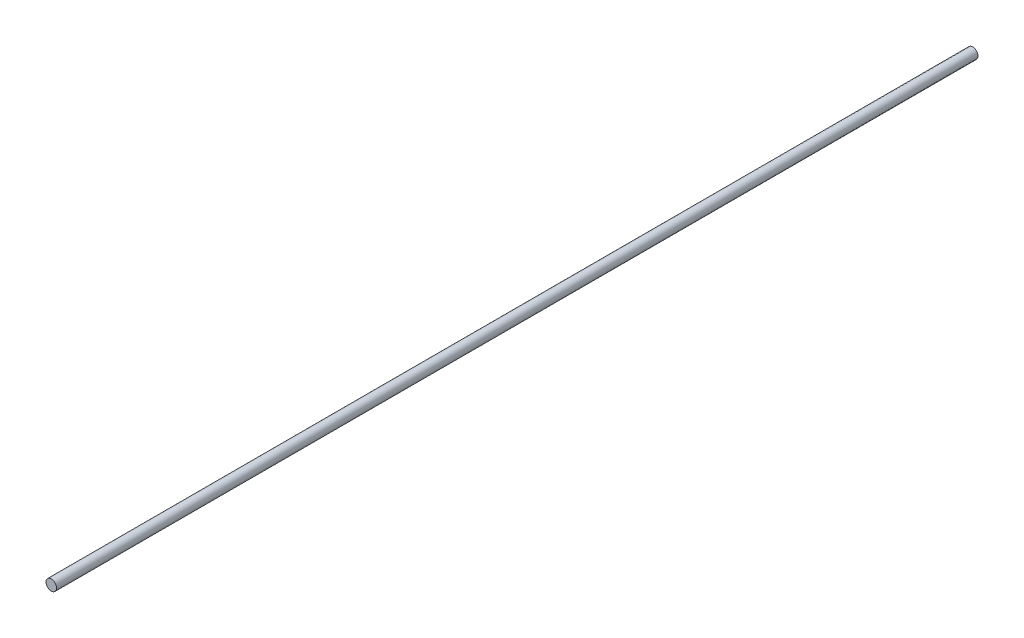
SolidWorks part; units mm, degrees
material "Plain Carbon Steel"
ref_plane "Front Plane" through (0, 0, 0) normal (0, 0, 1) x (1, 0, 0)
ref_plane "Top Plane" through (0, 0, 0) normal (0, 1, 0) x (1, 0, 0)
ref_plane "Right Plane" through (0, 0, 0) normal (1, 0, 0) x (0, 0, -1)
sketch "Sketch1" plane through (0, 0, 0) normal (0, 0, 1) x (1, 0, 0)
  circle A0 centre (0, 0) radius 4
  dimension "D1" = 8
extrude "Boss-Extrude1" add sketch "Sketch1" along normal blind 700
equation "\"D1@Boss-Extrude1\"=700"
